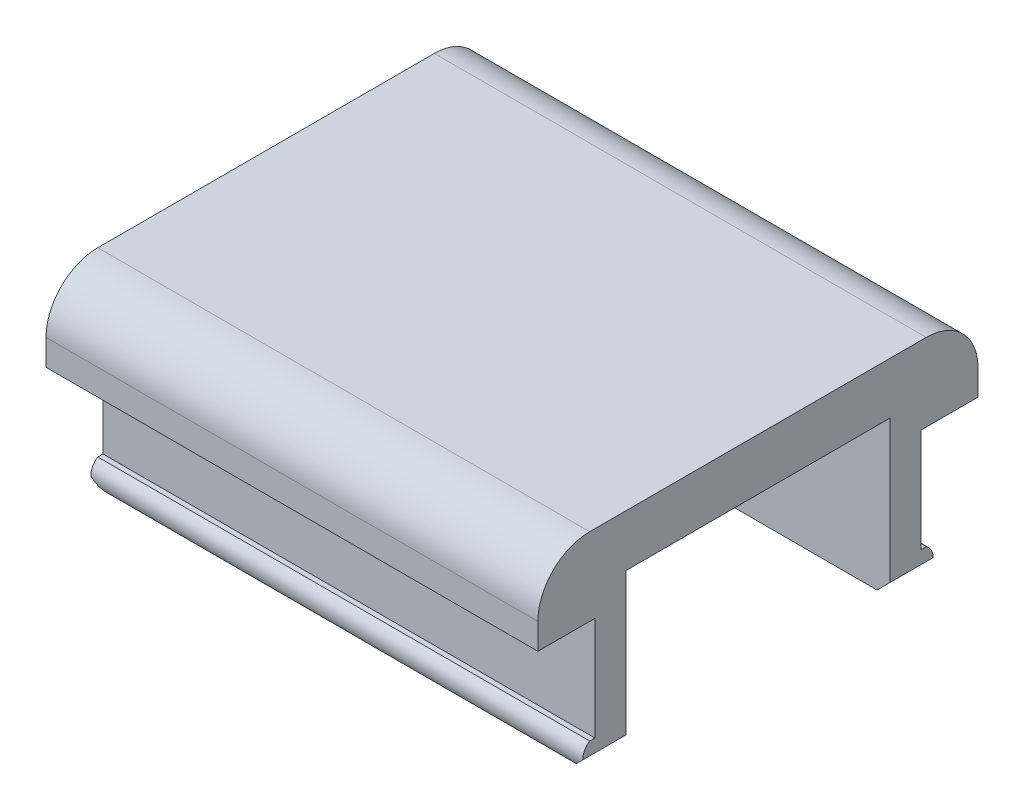
SolidWorks part; units mm, degrees
ref_plane "Front Plane" through (0, 0, 0) normal (0, 0, 1) x (1, 0, 0)
ref_plane "Top Plane" through (0, 0, 0) normal (0, 1, 0) x (1, 0, 0)
ref_plane "Right Plane" through (0, 0, 0) normal (1, 0, 0) x (0, 0, -1)
sketch "Sketch1" plane through (0, 0, 0) normal (1, 0, 0) x (0, 0, -1)
  line L1 (0, 0) -> (17, 0)
  line L2 (0, 0) -> (0, 3)
  line L3 (0, 3) -> (17, 3)
  line L4 (17, 0) -> (17, 3)
  dimension "D1" = 3
  dimension "D2" = 17
extrude "Boss-Extrude1" add sketch "Sketch1" along normal blind 19
fillet "Fillet1" radius 2 2 edges at (9.5, 3, -17) (9.5, 3, 0)
sketch "Sketch2" plane through (19, 0, 0) normal (1, 0, 0) x (0, 0, -1)
  line L0 (0, 0) -> (17, 0) construction
  line L1 (2, 0) -> (15, 0)
  line L2 (2, 0) -> (2, 1)
  line L3 (2, 1) -> (15, 1)
  line L4 (15, 0) -> (15, 1)
extrude "Cut-Extrude1" cut sketch "Sketch2" against normal through all
sketch "Sketch3" plane through (0, 1, 0) normal (0, -1, 0) x (-1, 0, 0)
  line L0 (-19, 15) -> (-19, 2) construction
  line L1 (0, 2) -> (-19, 2)
  line L2 (0, 2) -> (0, 2.6)
  line L3 (0, 2.6) -> (-19, 2.6)
  line L4 (-19, 2) -> (-19, 2.6)
  line L5 (0, 15) -> (0, 2) construction
  line L6 (-19, 15) -> (0, 15)
  line L7 (-19, 15) -> (-19, 14.4)
  line L8 (-19, 14.4) -> (0, 14.4)
  line L9 (0, 15) -> (0, 14.4)
  dimension "D1" = 0.6
extrude "Boss-Extrude2" add sketch "Sketch3" along normal blind 6 contours L3 L4 L1 L2 | L8 L9 L6 L7
sketch "Sketch4" plane through (19, 0, 0) normal (1, 0, 0) x (0, 0, -1)
  line L0 (2, -5) -> (2, -4)
  line L1 (2, -5) -> (2, 0) construction
  line L2 (15, -5) -> (15, -4)
  line L3 (15, -5) -> (15, 0) construction
  arc A0 (2, -5) -> (2, -4) centre (2.3317, -4.5) cw
  arc A1 (15, -5) -> (15, -4) centre (14.6683, -4.5) ccw
  dimension "D2" = 0.6
  dimension "D1" = 1
extrude "Boss-Extrude3" add sketch "Sketch4" against normal up to surface (19 mm away) up to face at (0, -0.6551, -8.5)
sketch "Sketch5" plane through (19, 0, 0) normal (1, 0, 0) x (0, 0, -1)
  line L0 (15, -5) -> (14.4, -5) construction
  line L1 (2.6, 1) -> (3.4, 1)
  line L2 (2.6, 1) -> (2.6, -5)
  line L3 (2.6, -5) -> (3.4, -5)
  line L4 (3.4, 1) -> (3.4, -5)
  line L5 (14.4, 1) -> (13.6, 1)
  line L6 (14.4, 1) -> (14.4, -5)
  line L7 (14.4, -5) -> (13.6, -5)
  line L8 (13.6, 1) -> (13.6, -5)
  dimension "D1" = 0.8
extrude "Boss-Extrude4" add sketch "Sketch5" against normal up to surface (19 mm away) up to face at (0, -1.0732, -8.5)
sketch "Sketch6" plane through (19, 0, 0) normal (1, 0, 0) x (0, 0, -1)
  line L1 (2, 0) -> (2.2, 0)
  line L2 (2, 0) -> (2, -4)
  line L3 (2, -4) -> (2.2, -4)
  line L4 (2.2, 0) -> (2.2, -4)
  line L5 (15, 0) -> (14.8, 0)
  line L6 (15, 0) -> (15, -4)
  line L7 (15, -4) -> (14.8, -4)
  line L8 (14.8, 0) -> (14.8, -4)
  dimension "D1" = 0.2
extrude "Cut-Extrude11" cut sketch "Sketch6" against normal up to surface (19 mm away) up to face at (0, -1.0732, -8.5)
chamfer "Chamfer1" distance 0.5 angle 45 4 edges at (19, -5, -14.3) (19, -5, -2.7) (0, -5, -2.7) (0, -5, -14.3)
